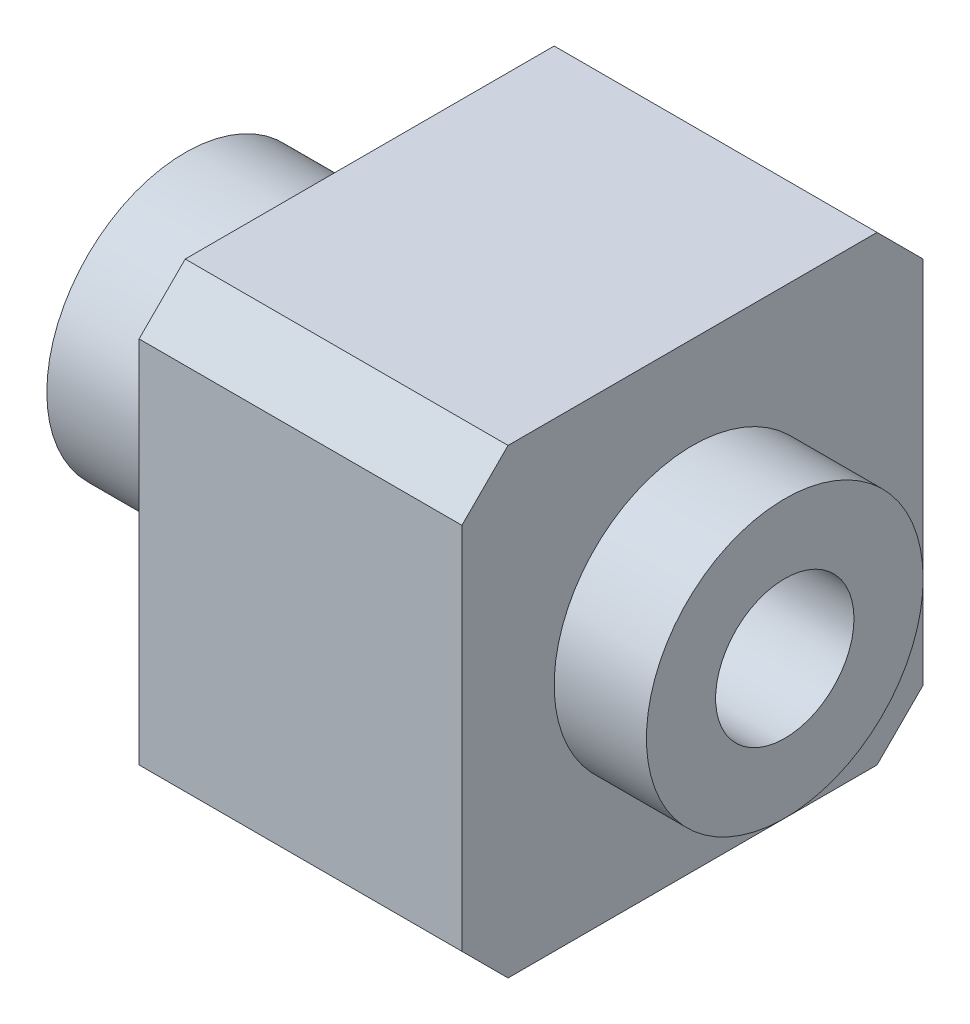
SolidWorks part; units mm, degrees
ref_plane "Front Plane" through (0, 0, 0) normal (0, 0, 1) x (1, 0, 0)
ref_plane "Top Plane" through (0, 0, 0) normal (0, 1, 0) x (1, 0, 0)
ref_plane "Right Plane" through (0, 0, 0) normal (1, 0, 0) x (0, 0, -1)
sketch "Sketch1" plane through (0, 0, 0) normal (1, 0, 0) x (0, 0, -1)
  line L5 (5, -5) -> (-5, -5)
  line L6 (5, -5) -> (5, 5)
  line L7 (5, 5) -> (-5, 5)
  line L8 (-5, -5) -> (-5, 5)
  line L9 (5, -5) -> (-5, 5) construction
  line L10 (5, 5) -> (-5, -5) construction
  point P0 (0, 0)
  dimension "D1" = 10
  dimension "D2" = 10
extrude "Boss-Extrude1" add sketch "Sketch1" against normal blind 13
sketch "Sketch2" plane through (0, 0, 0) normal (1, 0, 0) x (0, 0, -1)
  circle A0 centre (0, 0) radius 3
  circle A1 centre (0, 0) radius 15.3536
  dimension "D1" = 6
extrude "Cut-Extrude1" cut sketch "Sketch2" against normal blind 2
sketch "Sketch3" plane through (-13, 0, 0) normal (-1, 0, 0) x (0, 0, 1)
  circle A0 centre (0, 0) radius 3
  circle A1 centre (0, 0) radius 15.6354
  dimension "D1" = 6
extrude "Cut-Extrude2" cut sketch "Sketch3" against normal blind 4
sketch "Sketch4" plane through (0, 0, 0) normal (1, 0, 0) x (0, 0, -1)
  circle A0 centre (0, 0) radius 1.5
  dimension "D1" = 3
extrude "Cut-Extrude3" cut sketch "Sketch4" against normal through all
chamfer "Chamfer1" distance 1 angle 45 4 edges at (-5.5, -5, -5) (-5.5, 5, 5) (-5.5, -5, 5) (-5.5, 5, -5)
sketch "Sketch5" plane through (0, 0, 0) normal (0, 0, -1) x (-1, 0, 0)
  line L0 (0, 0) -> (5.5, 0) construction
  line L1 (0, 3) -> (0, -3) construction
  circle A0 centre (5.5, 0) radius 1.5
  dimension "D1" = 3
  dimension "D2" = 5.5
extrude "Cut-Extrude4" cut sketch "Sketch5" against normal blind 2 from offset 5
